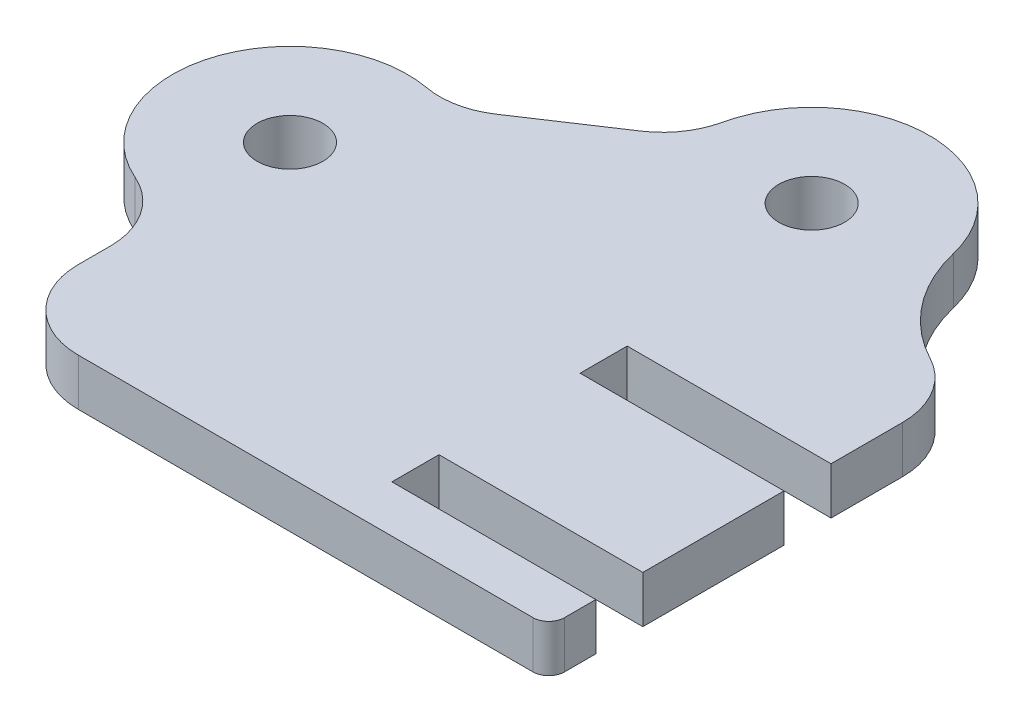
SolidWorks part; units mm, degrees
ref_plane "Front Plane" through (0, 0, 0) normal (0, 0, 1) x (1, 0, 0)
ref_plane "Top Plane" through (0, 0, 0) normal (0, 1, 0) x (1, 0, 0)
ref_plane "Right Plane" through (0, 0, 0) normal (1, 0, 0) x (0, 0, -1)
sketch "Sketch1" plane through (0, 0, 0) normal (0, 1, 0) x (1, 0, 0)
  line L0 (0, -11.4564) -> (0, -18.5)
  line L1 (0, -18.5) -> (30, -18.5)
  line L2 (30, -18.5) -> (30, -10.9559)
  line L3 (29.0642, -8.3847) -> (22.592, -0.6715)
  line L4 (0, 0) -> (20, 13.2665) construction
  line L5 (5.0178, 8.1284) -> (10.56, 11.8047)
  line L7 (-2.2111, 3.3333) -> (17.7889, 16.5998) construction
  circle A0 centre (0, 0) radius 2.1
  arc A1 (1.3524, 7.3771) -> (-3, -6.8739) centre (0, 0) ccw
  circle A2 centre (20, 13.2665) radius 2.1
  arc A3 (23.8533, 6.8321) -> (12.6777, 14.8894) centre (20, 13.2665) ccw
  arc A4 (5.0178, 8.1284) -> (1.3524, 7.3771) centre (2.254, 12.2951) cw
  arc A5 (10.56, 11.8047) -> (12.6777, 14.8894) centre (7.7962, 15.9714) ccw
  arc A6 (22.592, -0.6715) -> (23.8533, 6.8321) centre (26.4222, 2.5425) cw
  arc A7 (0, -11.4564) -> (-3, -6.8739) centre (-5, -11.4564) ccw
  arc A8 (30, -10.9559) -> (29.0642, -8.3847) centre (26, -10.9559) ccw
  point P26 (0, -7.5)
  point P29 (30, -9.5)
  dimension "D1" = 4.2
  dimension "D2" = 15
  dimension "D3" = 4.2
  dimension "D4" = 15
  dimension "D12" = 5
  dimension "D13" = 5
  dimension "D14" = 5
  dimension "D15" = 5
  dimension "D16" = 4
  dimension "D5" = 24
  dimension "D6" = 20
  dimension "D7" = 11
  dimension "D8" = 30
  dimension "D9" = 9
  dimension "D10" = 50
  dimension "D11" = 4
extrude "Boss-Extrude1" add sketch "Sketch1" along normal blind 3
fillet "Fillet1" radius 5 1 edges at (0, 1.5, 18.5)
sketch "Sketch2" plane through (0, 3, 0) normal (0, 1, 0) x (1, 0, 0)
  line L0 (30, -18.5) -> (30, -10.9559) construction
  line L1 (30, -12.5) -> (22, -12.5)
  line L2 (30, -12.5) -> (30, -15.5)
  line L3 (30, -15.5) -> (22, -15.5)
  line L4 (22, -12.5) -> (22, -15.5)
  line L5 (5, -18.5) -> (30, -18.5) construction
  dimension "D1" = 3
  dimension "D2" = 8
  dimension "D3" = 3
extrude "Cut-Extrude1" cut sketch "Sketch2" against normal blind 3
sketch "Sketch3" plane through (0, 3, 0) normal (0, 1, 0) x (1, 0, 0)
  line L0 (22, -12.5) -> (22, -15.5) construction
  line L1 (32, -0.5) -> (22, -0.5)
  line L2 (32, -0.5) -> (32, -3.5)
  line L3 (32, -3.5) -> (22, -3.5)
  line L4 (22, -0.5) -> (22, -3.5)
  line L5 (22, -15.5) -> (30, -15.5) construction
  dimension "D1" = 3
  dimension "D2" = 10
  dimension "D3" = 12
sketch "Sketch4" plane through (0, 3, 0) normal (0, 1, 0) x (1, 0, 0)
  line L0 (27.1269, 10.9305) -> (35, 7.21)
  line L1 (35, 7.21) -> (35, -0.5)
  line L2 (35, -18.5) -> (18.1019, -18.5)
  line L3 (5, -18.5) -> (30, -18.5) construction
  line L4 (18.1019, -18.5) -> (15.5268, 5.2656)
  line L5 (15.5268, 5.2656) -> (27.1269, 10.9305)
  line L7 (22, -12.5) -> (22, -15.5) construction
  line L8 (35, -15.5) -> (35, -18.5)
  line L9 (22, -12.5) -> (35, -12.5)
  line L10 (22, -12.5) -> (22, -15.5)
  line L11 (22, -15.5) -> (35, -15.5)
  line L12 (35, -3.5) -> (35, -12.5)
  line L13 (22, -3.5) -> (35, -3.5)
  line L14 (22, -3.5) -> (22, -0.5)
  line L15 (22, -0.5) -> (35, -0.5)
  arc A0 (23.8533, 6.8321) -> (12.6777, 14.8894) centre (20, 13.2665) ccw construction
  dimension "D1" = 13
  dimension "D2" = 3
  dimension "D3" = 3
extrude "Boss-Extrude2" add sketch "Sketch4" against normal blind 3
fillet "Fillet2" radius 10 1 edges at (27.1269, 1.5, -10.9305)
sketch "Sketch5" plane through (0, 3, 0) normal (0, 1, 0) x (1, 0, 0)
  line L1 (35, -0.5) -> (22, -0.5)
  line L2 (35, -0.5) -> (35, -3.5)
  line L3 (35, -3.5) -> (22, -3.5)
  line L4 (22, -0.5) -> (22, -3.5)
  dimension "D1" = 3
  dimension "D2" = 13
extrude "Cut-Extrude3" cut sketch "Sketch5" against normal blind 3.5
fillet "Fillet3" radius 5 1 edges at (35, 1.5, -7.21)
fillet "Fillet4" radius 1 1 edges at (35, 1.5, 18.5)
